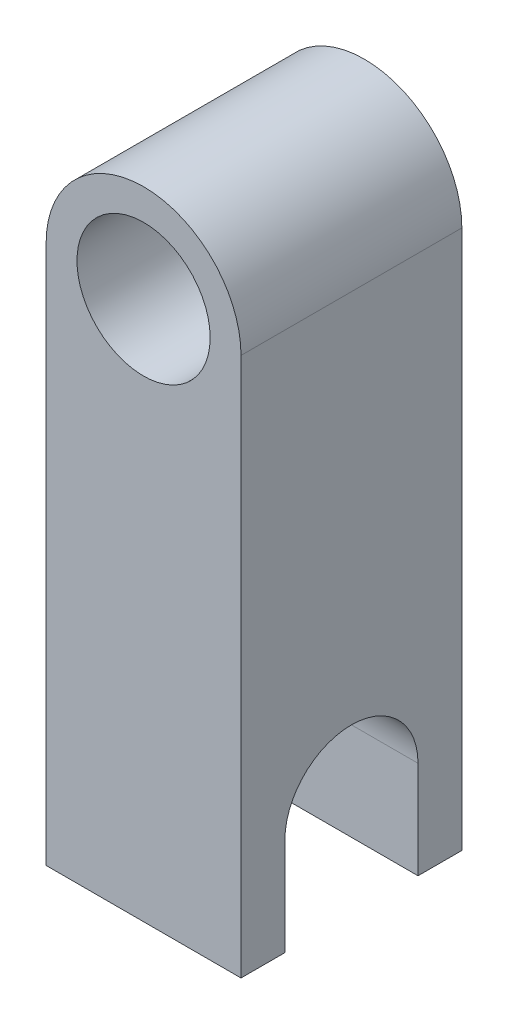
SolidWorks part; units mm, degrees
ref_plane "Front Plane" through (0, 0, 0) normal (0, 0, 1) x (1, 0, 0)
ref_plane "Top Plane" through (0, 0, 0) normal (0, 1, 0) x (1, 0, 0)
ref_plane "Right Plane" through (0, 0, 0) normal (1, 0, 0) x (0, 0, -1)
sketch "Sketch1" plane through (0, 0, 0) normal (0, 0, 1) x (1, 0, 0)
  line L0 (0, 0) -> (0, -68) construction
  line L1 (10.25, 0) -> (10.25, -68)
  line L2 (-10.25, 0) -> (-10.25, -68)
  line L3 (0, 0) -> (0, -68) construction
  line L4 (15, 0) -> (15, -68)
  line L5 (-15, 0) -> (-15, -68)
  arc A0 (10.25, 0) -> (-10.25, 0) centre (0, 0) ccw
  arc A1 (-10.25, -68) -> (10.25, -68) centre (0, -68) ccw
  arc A2 (15, 0) -> (-15, 0) centre (0, 0) ccw
  arc A3 (-15, -68) -> (15, -68) centre (0, -68) ccw
  circle A4 centre (0, 0) radius 10.25
  circle A5 centre (0, -68) radius 10.25
  point P3 (0, -34)
  point P10 (0, -34)
  dimension "D2" = 10.25
  dimension "D3" = 15
  dimension "D1" = 68
extrude "Boss-Extrude1" add sketch "Sketch1" along normal blind 34 contours L5 A3 L4 A2 A1 L2 A0 L1 | A5 L1 A4 L2 | A1 A5
sketch "Sketch2" plane through (-15, 0, 0) normal (-1, 0, 0) x (0, 0, 1)
  line L1 (34, -83) -> (0, -83)
  line L2 (34, -83) -> (34, -68)
  line L3 (34, -68) -> (0, -68)
  line L4 (0, -83) -> (0, -68)
extrude "Boss-Extrude2" add sketch "Sketch2" against normal blind 30
sketch "Sketch3" plane through (-15, 0, 0) normal (-1, 0, 0) x (0, 0, 1)
  line L0 (17, 0) -> (17, -68) construction
  line L1 (34, 0) -> (0, 0) construction
  circle A0 centre (17, -68) radius 10.25
  dimension "D1" = 68
extrude "Cut-Extrude1" cut sketch "Sketch3" against normal blind 30
sketch "Sketch4" plane through (-15, 0, 0) normal (-1, 0, 0) x (0, 0, 1)
  line L0 (0, -83) -> (34, -83) construction
  line L1 (6.75, -68) -> (27.25, -68)
  line L2 (6.75, -68) -> (6.75, -83)
  line L3 (6.75, -83) -> (27.25, -83)
  line L4 (27.25, -68) -> (27.25, -83)
  circle A0 centre (17, -68) radius 10.25 construction
extrude "Cut-Extrude2" cut sketch "Sketch4" against normal blind 34
